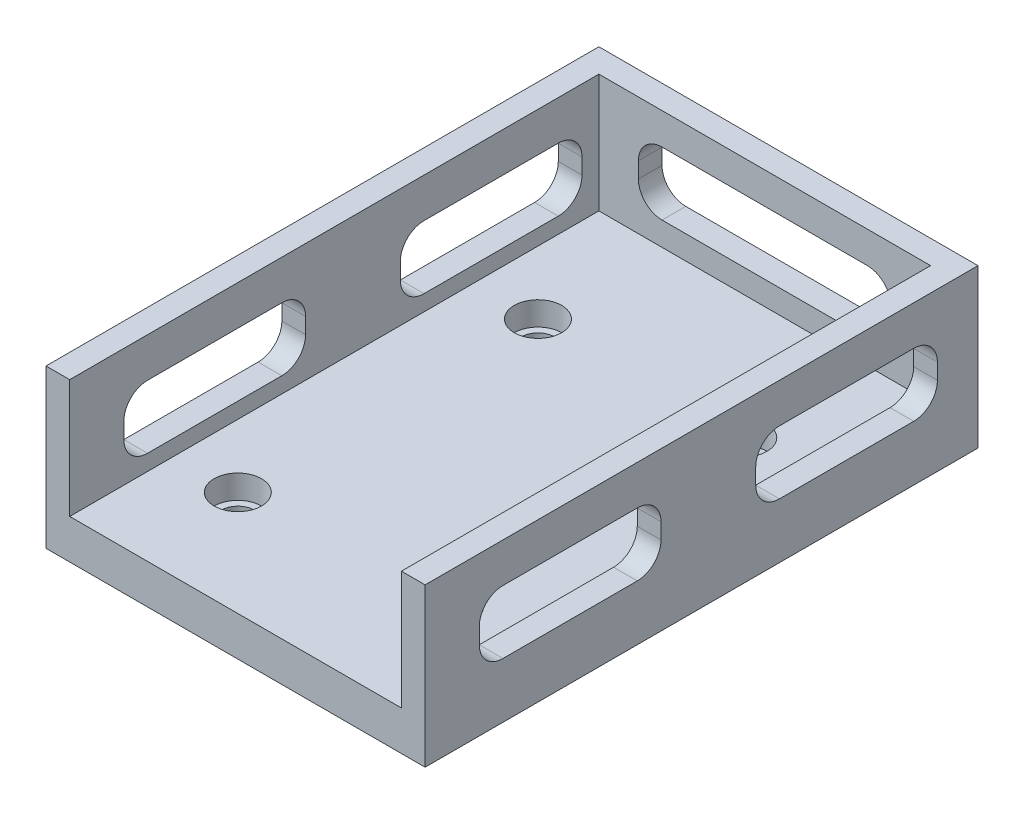
SolidWorks part; units mm, degrees
ref_plane "前视基准面" through (0, 0, 0) normal (0, 0, 1) x (1, 0, 0)
ref_plane "上视基准面" through (0, 0, 0) normal (0, 1, 0) x (1, 0, 0)
ref_plane "右视基准面" through (0, 0, 0) normal (1, 0, 0) x (0, 0, -1)
other "Configuration Table"
sketch "草图1" plane through (0, 0, 0) normal (0, 0, 1) x (1, 0, 0)
  line L0 (0, 29.1978) -> (0, -24.1566) construction
  line L1 (0, -15.1693) -> (-24, -15.1693)
  line L2 (-24, -15.1693) -> (-24, -10.1693)
  line L3 (-24, -10.1693) -> (0, -10.1693)
  line L4 (0, -10.1693) -> (24, -10.1693)
  line L5 (24, -10.1693) -> (24, -15.1693)
  line L6 (24, -15.1693) -> (0, -15.1693)
  dimension "D1" = 5
  dimension "D2" = 24
  dimension "D3" = 24
extrude "凸台-拉伸1" add sketch "草图1" along normal blind 70
sketch "草图2" plane through (0, 0, 0) normal (0, 0, -1) x (-1, 0, 0)
  line L0 (-24, -10.1693) -> (-24, 4.8307)
  line L1 (-24, 4.8307) -> (-21, 4.8307)
  line L2 (-21, 4.8307) -> (-21, -10.1693)
  line L3 (-24, -10.1693) -> (24, -10.1693) construction
  line L4 (0, 12.5121) -> (0, -18.7112) construction
  line L5 (24, -10.1693) -> (24, 4.8307)
  line L6 (24, 4.8307) -> (21, 4.8307)
  line L7 (21, 4.8307) -> (21, -10.1693)
  line L8 (-24, -10.1693) -> (-21, -10.1693)
  line L9 (21, -10.1693) -> (24, -10.1693)
  dimension "D1" = 3
  dimension "D2" = 3
  dimension "D3" = 15
  dimension "D4" = 15
extrude "凸台-拉伸2" add sketch "草图2" against normal blind 70
sketch "草图3" plane through (21, 0, 0) normal (-1, 0, 0) x (0, 0, 1)
  line L0 (0, 4.8307) -> (0, -10.1693)
  line L1 (0, 4.8307) -> (0, -15.1693) construction
  line L2 (0, -10.1693) -> (3, -10.1693)
  line L3 (3, -10.1693) -> (3, 4.8307)
  line L4 (70, 4.8307) -> (0, 4.8307) construction
  line L5 (3, 4.8307) -> (0, 4.8307)
  line L6 (70, -15.1693) -> (0, -15.1693) construction
  dimension "D1" = 5
  dimension "D2" = 3
extrude "凸台-拉伸3" add sketch "草图3" along normal up to next
sketch "草图4" plane through (-24, 0, 0) normal (-1, 0, 0) x (0, 0, 1)
  line L0 (5.1403, -3.1693) -> (5.1403, -5.1693)
  line L1 (8.1403, -8.1693) -> (25.1403, -8.1693)
  line L2 (28.1403, -5.1693) -> (28.1403, -3.1693)
  line L3 (25.1403, -0.1693) -> (8.1403, -0.1693)
  line L4 (40.1403, -3.1693) -> (40.1403, -5.1693)
  line L5 (43.1403, -8.1693) -> (60.1403, -8.1693)
  line L6 (63.1403, -5.1693) -> (63.1403, -3.1693)
  line L7 (60.1403, -0.1693) -> (43.1403, -0.1693)
  line L8 (70, -15.1693) -> (0, -15.1693) construction
  arc A0 (63.1403, -3.1693) -> (60.1403, -0.1693) centre (60.1403, -3.1693) ccw
  arc A1 (63.1403, -5.1693) -> (60.1403, -8.1693) centre (60.1403, -5.1693) cw
  arc A2 (40.1403, -5.1693) -> (43.1403, -8.1693) centre (43.1403, -5.1693) ccw
  arc A3 (43.1403, -0.1693) -> (40.1403, -3.1693) centre (43.1403, -3.1693) ccw
  arc A4 (25.1403, -0.1693) -> (28.1403, -3.1693) centre (25.1403, -3.1693) cw
  arc A5 (25.1403, -8.1693) -> (28.1403, -5.1693) centre (25.1403, -5.1693) ccw
  arc A6 (8.1403, -8.1693) -> (5.1403, -5.1693) centre (8.1403, -5.1693) cw
  arc A7 (5.1403, -3.1693) -> (8.1403, -0.1693) centre (8.1403, -3.1693) cw
  point P12 (63.1403, -0.1693)
  point P15 (63.1403, -8.1693)
  point P20 (40.1403, -0.1693)
  point P23 (28.1403, -0.1693)
  point P28 (5.1403, -8.1693)
  point P31 (5.1403, -0.1693)
  dimension "D8" = 3
  dimension "D1" = 7
  dimension "D2" = 8
  dimension "D3" = 12
  dimension "D4" = 7
  dimension "D5" = 8
  dimension "D6" = 23
  dimension "D7" = 23
extrude "切除-拉伸1" cut sketch "草图4" against normal through all
sketch "草图5" plane through (0, 0, 3) normal (0, 0, 1) x (1, 0, 0)
  line L0 (0, 10.6396) -> (0, -7.0324) construction
  line L1 (-13, 0.8307) -> (13, 0.8307)
  line L2 (16, -2.1693) -> (16, -4.1693)
  line L3 (13, -7.1693) -> (-13, -7.1693)
  line L4 (-16, -4.1693) -> (-16, -2.1693)
  line L5 (-21, 4.8307) -> (21, 4.8307) construction
  line L6 (-21, -10.1693) -> (21, -10.1693) construction
  arc A0 (13, 0.8307) -> (16, -2.1693) centre (13, -2.1693) cw
  arc A1 (16, -4.1693) -> (13, -7.1693) centre (13, -4.1693) cw
  arc A2 (-16, -4.1693) -> (-13, -7.1693) centre (-13, -4.1693) ccw
  arc A3 (-16, -2.1693) -> (-13, 0.8307) centre (-13, -2.1693) cw
  dimension "D5" = 3
  dimension "D1" = 16
  dimension "D2" = 16
  dimension "D3" = 4
  dimension "D4" = 3
extrude "切除-拉伸2" cut sketch "草图5" against normal through all
sketch "草图6" plane through (0, -10.1693, 0) normal (0, 1, 0) x (1, 0, 0)
  line L0 (0, -7.6376) -> (0, -65.8636) construction
  circle A0 centre (-13, -18.7147) radius 3
  circle A1 centre (13, -18.7147) radius 3
  circle A2 centre (-13, -56.7147) radius 3
  circle A3 centre (13, -55.8516) radius 3
  dimension "D1" = 6
  dimension "D2" = 6
  dimension "D3" = 13
  dimension "D4" = 13
  dimension "D5" = 6
  dimension "D6" = 6
  dimension "D7" = 38
extrude "切除-拉伸3" cut sketch "草图6" against normal blind 3
sketch "草图7" plane through (0, -13.1693, 0) normal (0, 1, 0) x (1, 0, 0)
  circle A0 centre (-13, -18.7147) radius 2.1
  circle A1 centre (13, -18.7147) radius 2.1
  circle A2 centre (13, -55.8516) radius 2.1
  circle A3 centre (-13, -56.7147) radius 2.1
  dimension "D1" = 4.2
extrude "切除-拉伸4" cut sketch "草图7" against normal through all
